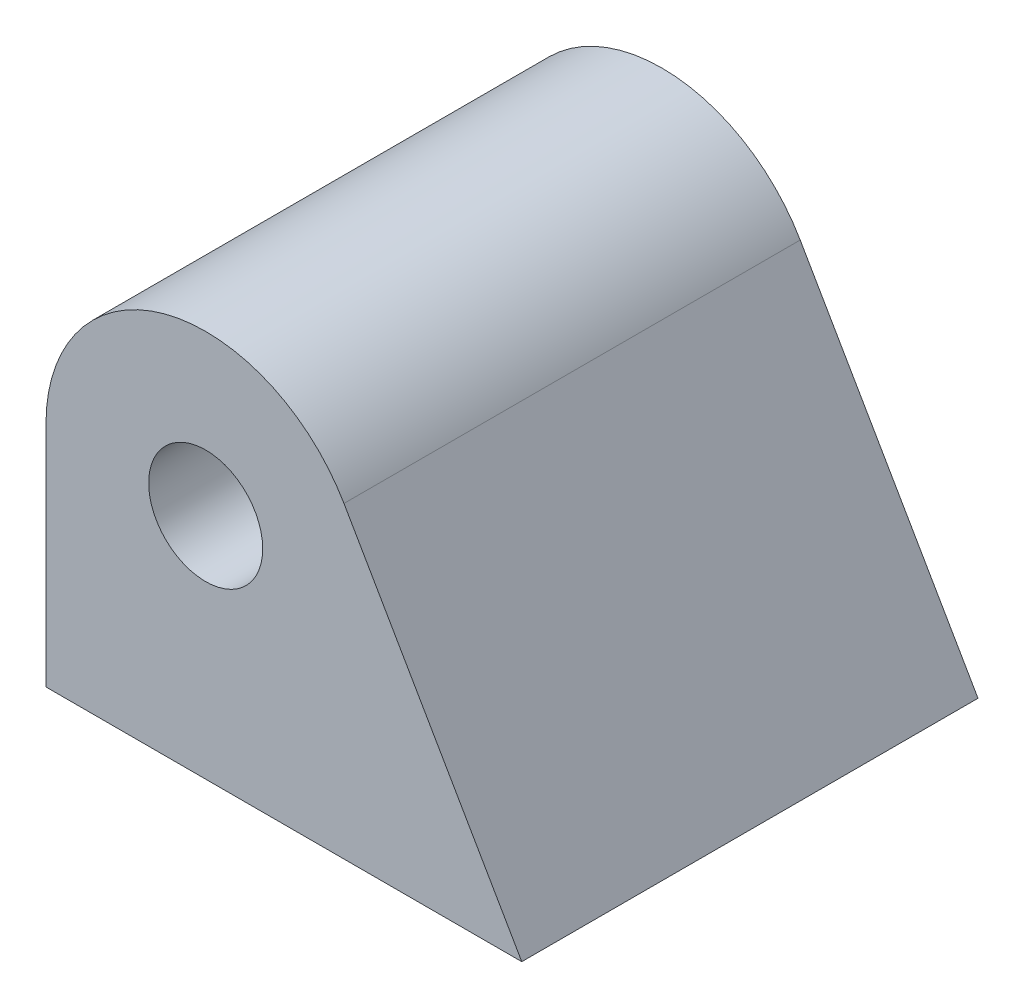
SolidWorks part; units mm, degrees
ref_plane "Front Plane" through (0, 0, 0) normal (0, 0, 1) x (1, 0, 0)
ref_plane "Top Plane" through (0, 0, 0) normal (0, 1, 0) x (1, 0, 0)
ref_plane "Right Plane" through (0, 0, 0) normal (1, 0, 0) x (0, 0, -1)
sketch "Sketch1" plane through (0, 0, 0) normal (0, 0, 1) x (1, 0, 0)
  line L1 (0, 0) -> (26.4876, 0)
  line L2 (0, 0) -> (0, 12.7)
  line L4 (26.4876, 0) -> (16.589, 17.145)
  arc A0 (0, 12.7) -> (16.589, 17.145) centre (8.89, 12.7) cw
  circle A1 centre (8.89, 12.7) radius 3.175
  point P7 (58.849, 0)
  dimension "D3" = 6.35
  dimension "D4" = 8.89
  dimension "D1" = 30
  dimension "D2" = 12.7
extrude "Boss-Extrude1" add sketch "Sketch1" along normal blind 25.4
